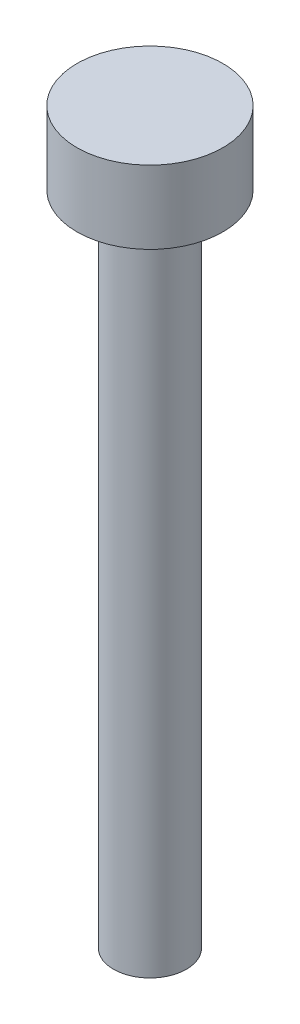
SolidWorks part; units mm, degrees
ref_plane "Front Plane" through (0, 0, 0) normal (0, 0, 1) x (1, 0, 0)
ref_plane "Top Plane" through (0, 0, 0) normal (0, 1, 0) x (1, 0, 0)
ref_plane "Right Plane" through (0, 0, 0) normal (1, 0, 0) x (0, 0, -1)
sketch "Sketch2" plane through (0, 0, 0) normal (0, 1, 0) x (1, 0, 0)
  circle A0 centre (0, 0) radius 5
  dimension "D1" = 10
extrude "Boss-Extrude1" add sketch "Sketch2" along normal blind 5
sketch "Sketch3" plane through (0, 0, 0) normal (0, -1, 0) x (1, 0, 0)
  circle A0 centre (0, 0) radius 2.5
  dimension "D1" = 5
extrude "Boss-Extrude2" add sketch "Sketch3" along normal blind 45
